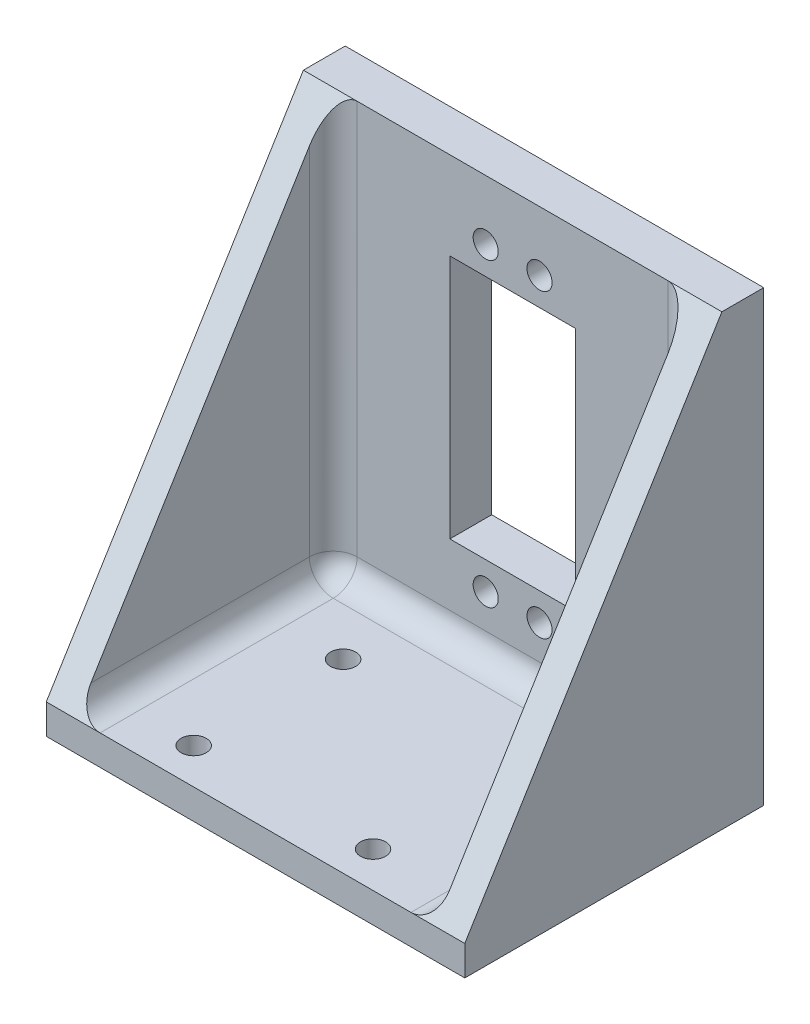
SolidWorks part; units mm, degrees
ref_plane "Front Plane" through (0, 0, 0) normal (0, 0, 1) x (1, 0, 0)
ref_plane "Top Plane" through (0, 0, 0) normal (0, 1, 0) x (1, 0, 0)
ref_plane "Right Plane" through (0, 0, 0) normal (1, 0, 0) x (0, 0, -1)
sketch "Sketch1" plane through (0, 0, 0) normal (0, 1, 0) x (1, 0, 0)
  line L1 (-35, -25) -> (35, -25)
  line L2 (-35, -25) -> (-35, 25)
  line L3 (-35, 25) -> (35, 25)
  line L4 (35, -25) -> (35, 25)
  line L5 (-35, -25) -> (35, 25) construction
  line L6 (-35, 25) -> (35, -25) construction
  point P0 (0, 0)
  dimension "D1" = 50
  dimension "D2" = 70
extrude "Boss-Extrude1" add sketch "Sketch1" along normal blind 5
sketch "Sketch2" plane through (0, 5, 0) normal (0, 1, 0) x (1, 0, 0)
  line L0 (35, -25) -> (35, 25) construction
  line L1 (-35, 25) -> (35, 25)
  line L2 (-35, 25) -> (-35, 18)
  line L3 (-35, 18) -> (35, 18)
  line L4 (35, 25) -> (35, 18)
  dimension "D1" = 7
extrude "Boss-Extrude2" add sketch "Sketch2" along normal blind 70
sketch "Sketch3" plane through (0, 0, -25) normal (0, 0, -1) x (-1, 0, 0)
  line L0 (0, 75) -> (0, 0) construction
  line L1 (-35, 75) -> (35, 75) construction
  line L2 (-10.5, 19.35) -> (-10.5, 60.35)
  line L3 (-10.5, 19.35) -> (10.5, 19.35)
  line L4 (-10.5, 60.35) -> (10.5, 60.35)
  line L5 (10.5, 19.35) -> (10.5, 60.35)
  line L6 (-10.5, 19.35) -> (10.5, 60.35) construction
  line L7 (-10.5, 60.35) -> (10.5, 19.35) construction
  line L8 (0, 39.85) -> (10.5, 39.85) construction
  circle A0 centre (-4.5, 65) radius 2.1
  circle A1 centre (4.5, 65) radius 2.1
  circle A2 centre (4.5, 14.7) radius 2.1
  circle A3 centre (-4.5, 14.7) radius 2.1
  point P7 (0, 39.85)
  dimension "D5" = 4.2
  dimension "D6" = 6
  dimension "D7" = 4.65
  dimension "D1" = 21
  dimension "D2" = 41
  dimension "D3" = 10.5
  dimension "D4" = 14.65
extrude "Cut-Extrude1" cut sketch "Sketch3" against normal blind 70
sketch "Sketch6" plane through (-35, 0, 0) normal (-1, 0, 0) x (0, 0, 1)
  line L0 (-18, 75) -> (25, 5)
  line L1 (25, 5) -> (-18, 5)
  line L2 (-18, 5) -> (-18, 75)
extrude "Boss-Extrude3" add sketch "Sketch6" against normal blind 5
sketch "Sketch7" plane through (35, 0, 0) normal (1, 0, 0) x (0, 0, -1)
  line L0 (18, 75) -> (-25, 5)
  line L1 (-25, 5) -> (18, 5)
  line L2 (18, 5) -> (18, 75)
extrude "Boss-Extrude4" add sketch "Sketch7" against normal blind 5
sketch "Sketch8" plane through (0, 5, 0) normal (0, 1, 0) x (1, 0, 0)
  line L0 (-30, 18) -> (30, 18) construction
  circle A0 centre (-16.348, 6) radius 2.1
  circle A1 centre (13.652, 6) radius 2.1
  circle A2 centre (-16.348, -19) radius 2.1
  circle A3 centre (13.652, -19) radius 2.1
  dimension "D1" = 4.2
  dimension "D2" = 4.2
  dimension "D3" = 4.2
  dimension "D4" = 4.2
  dimension "D5" = 25
  dimension "D6" = 12
  dimension "D7" = 12
  dimension "D8" = 25
  dimension "D9" = 30
  dimension "D10" = 30
extrude "Cut-Extrude2" cut sketch "Sketch8" against normal blind 5
fillet "Fillet1" radius 4 1 edges at (0, 5, -18)
fillet "Fillet2" radius 4 6 edges at (-30, 5, 5.5) (-30, 6.1716, -16.8284) (30, 5, 5.5) (30, 6.1716, -16.8284) (-30, 42, -18) (30, 42, -18)
